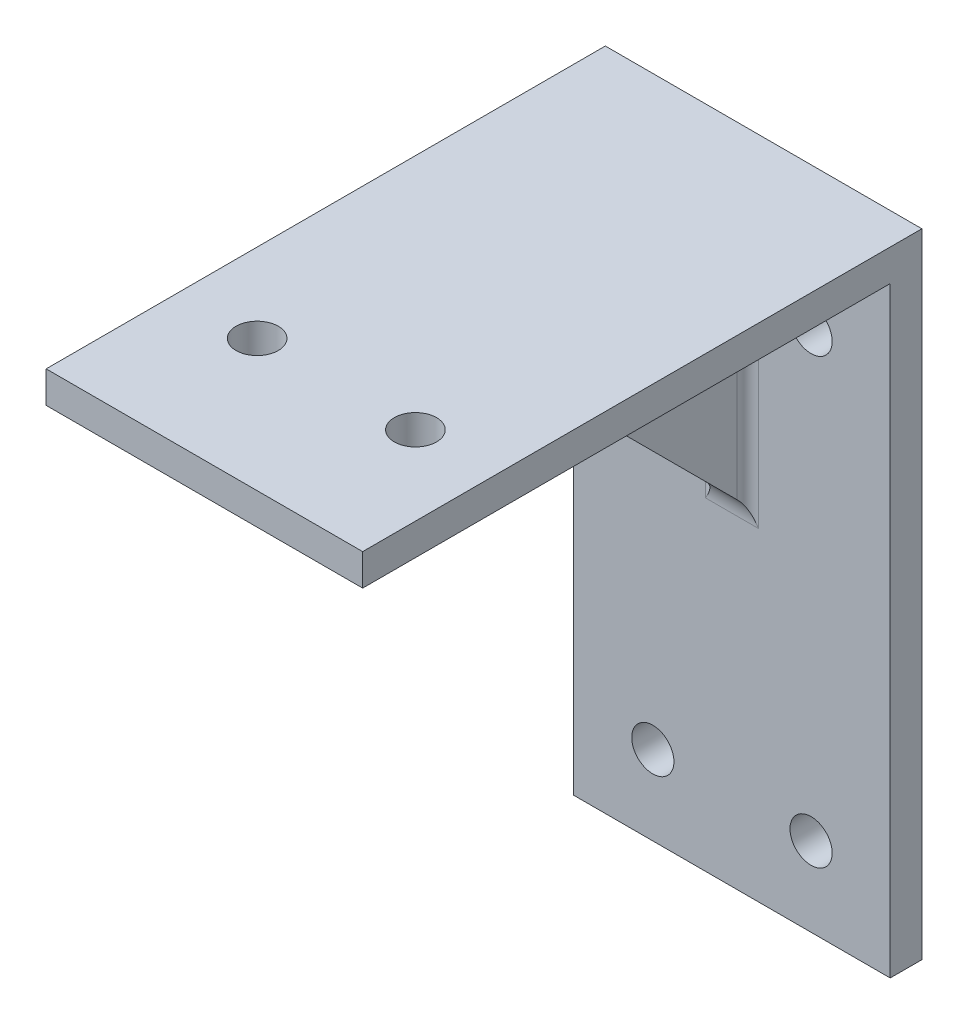
SolidWorks part; units mm, degrees
material "6061-T6 (SS)"
ref_plane "Front Plane" through (0, 0, 0) normal (1, 0, 0) x (0, 1, 0)
ref_plane "Top Plane" through (0, 0, 0) normal (0, 0, 1) x (0, 1, 0)
ref_plane "Right Plane" through (0, 0, 0) normal (0, 1, 0) x (-1, 0, 0)
sketch "Sketch1" plane through (0, 0, 0) normal (0, 0, 1) x (0, 1, 0)
  line L1 (-60, 30) -> (60, 30)
  line L2 (-60, 30) -> (-60, -30)
  line L3 (-60, -30) -> (60, -30)
  line L4 (60, 30) -> (60, -30)
  line L5 (-60, 30) -> (60, -30) construction
  line L6 (-60, -30) -> (60, 30) construction
  point P0 (0, 0)
  dimension "D1" = 120
  dimension "D2" = 60
extrude "Boss-Extrude1" add sketch "Sketch1" along normal blind 6
sketch "Sketch2" plane through (0, 60, 0) normal (0, 1, 0) x (-1, 0, 0)
  line L1 (-30, 106) -> (30, 106)
  line L2 (-30, 106) -> (-30, 6)
  line L3 (-30, 6) -> (30, 6)
  line L4 (30, 106) -> (30, 6)
  line L5 (-30, 106) -> (30, 6) construction
  line L6 (-30, 6) -> (30, 106) construction
  point P0 (0, 56)
  dimension "D1" = 60
  dimension "D2" = 100
extrude "Boss-Extrude2" add sketch "Sketch2" against normal blind 6
sketch "Sketch4" plane through (0, 0, 0) normal (1, 0, 0) x (0, 1, 0)
  line L0 (54, 6) -> (4, 6)
  line L1 (-60, 6) -> (54, 6) construction
  line L2 (4, 6) -> (54, 56)
  line L3 (54, 106) -> (54, 6) construction
  line L4 (54, 56) -> (54, 6)
  dimension "D1" = 50
  dimension "D2" = 50
extrude "Boss-Extrude3" add sketch "Sketch4" along normal mid plane 6
sketch "Sketch5" plane through (0, 60, 0) normal (0, 1, 0) x (-1, 0, 0)
  line L0 (-30, 0) -> (30, 0) construction
  circle A0 centre (-15, 81) radius 4
  circle A1 centre (15, 81) radius 4
  dimension "D2" = 81
  dimension "D6" = 81
extrude "Cut-Extrude2" cut sketch "Sketch5" against normal blind 62
sketch "Sketch6" plane through (0, 0, 6) normal (0, 0, 1) x (1, 0, 0)
  line L0 (-30, -60) -> (30, -60) construction
  line L1 (-30, 54) -> (-30, -60) construction
  line L2 (30, -60) -> (30, 54) construction
  line L3 (-30, 54) -> (30, 54) construction
  circle A0 centre (-15, -45) radius 4
  circle A1 centre (15, -45) radius 4
  circle A2 centre (-15, 39) radius 4
  circle A3 centre (15, 39) radius 4
  dimension "D5" = 8
  dimension "D6" = 8
  dimension "D10" = 8
  dimension "D11" = 8
  dimension "D1" = 15
  dimension "D2" = 15
  dimension "D3" = 15
  dimension "D4" = 15
  dimension "D7" = 15
  dimension "D8" = 15
  dimension "D9" = 15
extrude "Cut-Extrude3" cut sketch "Sketch6" against normal blind 62
fillet "Fillet1" radius 2 4 edges at (-3, 29, 6) (3, 29, 6) (3, 54, 31) (-3, 54, 31)
fillet "Fillet3" radius 6.5 2 edges at (0, 4, 6) (0, 54, 56)
